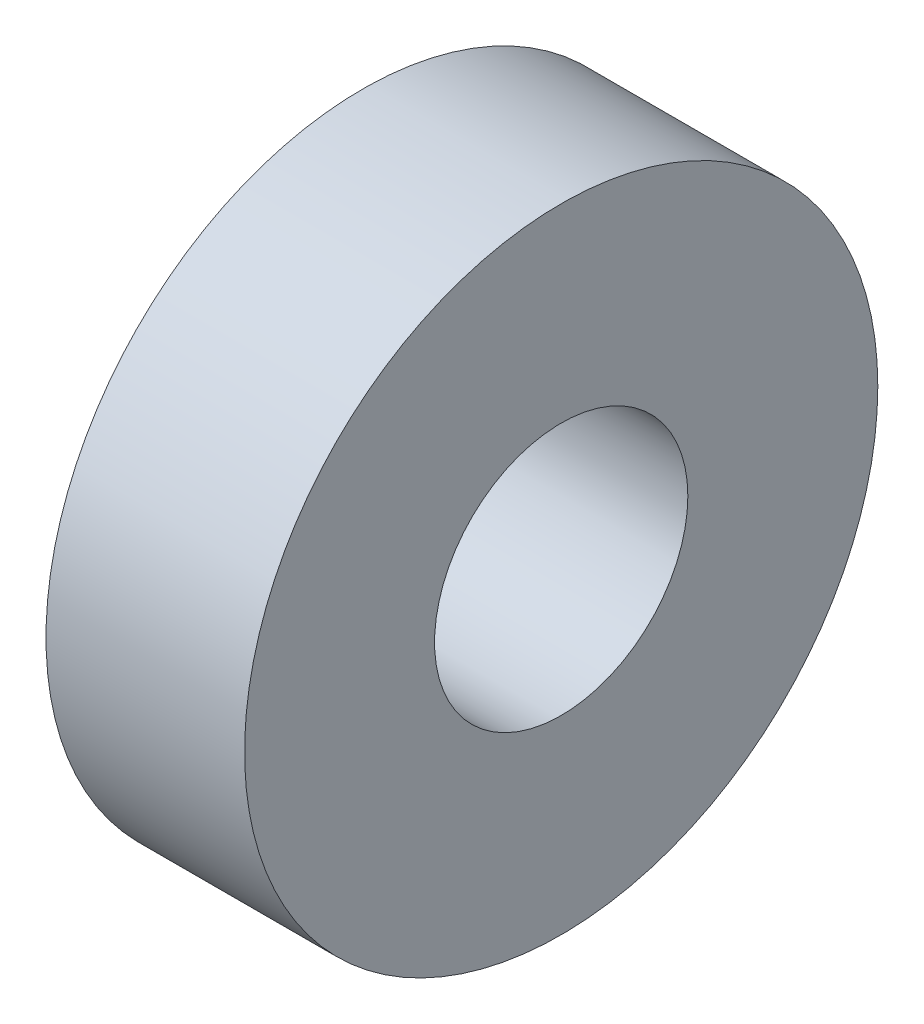
SolidWorks part; units mm, degrees
material "AISI 304"
ref_plane "Front Plane" through (0, 0, 0) normal (0, 0, 1) x (1, 0, 0)
ref_plane "Top Plane" through (0, 0, 0) normal (0, 1, 0) x (1, 0, 0)
ref_plane "Right Plane" through (0, 0, 0) normal (1, 0, 0) x (0, 0, -1)
sketch "Sketch1" plane through (0, 0, 0) normal (1, 0, 0) x (0, 0, -1)
  circle A0 centre (0, 0) radius 3.175
  circle A1 centre (0, 0) radius 7.9375
  dimension "D1" = 6.35
  dimension "D2" = 15.875
extrude "Boss-Extrude1" add sketch "Sketch1" along normal mid plane 4.9784
sketch "Sketch2" plane through (2.4892, 0, 0) normal (1, 0, 0) x (0, 0, -1)
  circle A0 centre (0, 0) radius 4.445
  circle A1 centre (0, 0) radius 6.6675
  circle A2 centre (0, 0) radius 7.9375 construction
  circle A3 centre (0, 0) radius 3.175 construction
  dimension "D1" = 1.27
  dimension "D2" = 1.27
extrude "Cut-Extrude1" [suppressed] cut sketch "Sketch2" against normal blind 0.254
mirror "Mirror1" [suppressed] about plane through (0, 0, 0) normal (1, 0, 0)
